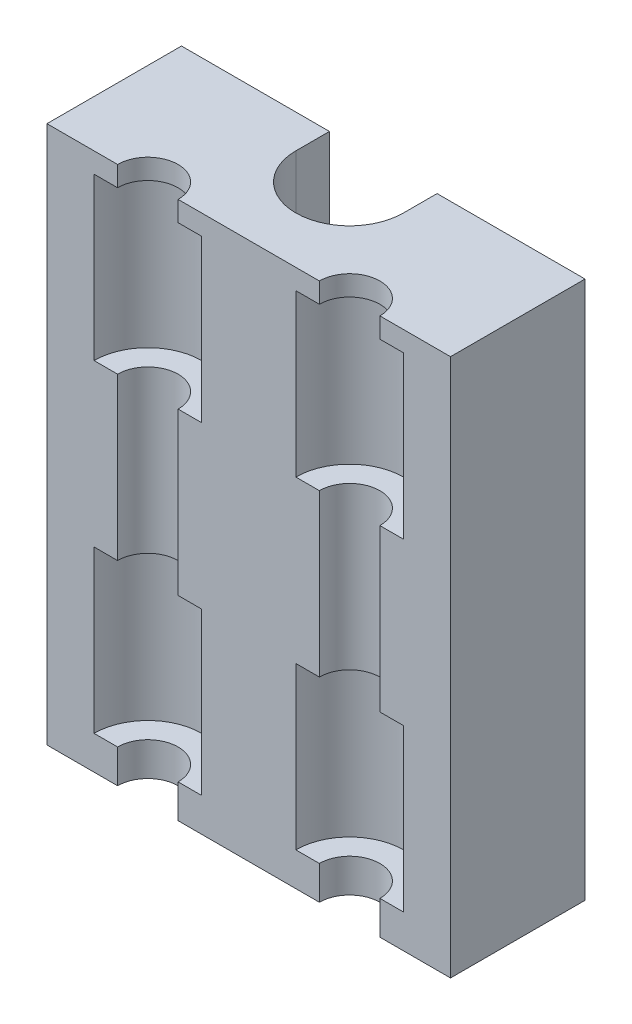
SolidWorks part; units mm, degrees
ref_plane "前视基准面" through (0, 0, 0) normal (0, 0, 1) x (1, 0, 0)
ref_plane "上视基准面" through (0, 0, 0) normal (0, 1, 0) x (1, 0, 0)
ref_plane "右视基准面" through (0, 0, 0) normal (1, 0, 0) x (0, 0, -1)
sketch "草图1" plane through (0, 0, 0) normal (0, 1, 0) x (1, 0, 0)
  line L0 (0, 0) -> (0, 5) construction
  line L2 (-15, 10) -> (15, 10)
  line L3 (-15, 10) -> (-15, 0)
  line L4 (-15, 0) -> (15, 0)
  line L5 (15, 10) -> (15, 0)
  line L6 (-15, 10) -> (15, 0) construction
  line L7 (-15, 0) -> (15, 10) construction
  point P7 (0, 0)
  dimension "D1" = 30
  dimension "D2" = 10
extrude "凸台-拉伸1" add sketch "草图1" against normal blind 40
sketch "草图2" plane through (0, 0, 0) normal (0, 1, 0) x (1, 0, 0)
  line L0 (-15, 0) -> (15, 0) construction
  line L1 (0, 0) -> (0, 3.0438) construction
  circle A0 centre (-7.5, 0) radius 4
  circle A1 centre (7.5, 0) radius 4
  point P9 (-9.2259, 0)
  dimension "D1" = 8
  dimension "D2" = 15
extrude "切除-拉伸1" cut sketch "草图2" against normal blind 12 from offset 1.5 offset against normal yes
sketch "草图3" plane through (0, -13.5, 0) normal (0, 1, 0) x (1, 0, 0)
  line L1 (-11.5, 0) -> (-3.5, 0)
  line L2 (-11.5, 0) -> (-3.5, 0)
  line L3 (3.5, 0) -> (11.5, 0)
  line L4 (3.5, 0) -> (11.5, 0)
  arc A1 (-3.5, 0) -> (-11.5, 0) centre (-7.5, 0) ccw
  arc A2 (-3.5, 0) -> (-11.5, 0) centre (-7.5, 0) ccw
  arc A3 (11.5, 0) -> (3.5, 0) centre (7.5, 0) ccw
  arc A4 (11.5, 0) -> (3.5, 0) centre (7.5, 0) ccw
  dimension "D1" = 0
  dimension "D2" = 0
extrude "切除-拉伸2" cut sketch "草图3" against normal blind 12 from offset 12 offset against normal yes
sketch "草图4" plane through (0, -13.5, 0) normal (0, 1, 0) x (1, 0, 0)
  line L0 (-3.5, 0) -> (-11.5, 0) construction
  line L1 (3.5, 0) -> (11.5, 0) construction
  circle A0 centre (-7.5, 0) radius 2.25
  circle A1 centre (7.5, 0) radius 2.25
  dimension "D1" = 4.5
extrude "切除-拉伸3" cut sketch "草图4" against normal through all both and the other way through all
sketch "草图5" plane through (0, 0, 0) normal (0, 1, 0) x (1, 0, 0)
  line L0 (0, 0) -> (0, 10) construction
  line L1 (0, 7.5) -> (0, 10) construction
  line L2 (-4, 7.5) -> (-4, 10)
  line L3 (4, 7.5) -> (4, 10)
  line L4 (15, 10) -> (-15, 10) construction
  arc A0 (-4, 7.5) -> (4, 7.5) centre (0, 7.5) ccw
  arc A1 (4, 10) -> (-4, 10) centre (0, 10) ccw
  point P3 (0, 8.75)
  point P9 (2.9872, 10)
  point P12 (0, 7.2999)
  dimension "D1" = 4
  dimension "D2" = 2.5
extrude "切除-拉伸4" cut sketch "草图5" against normal through all
